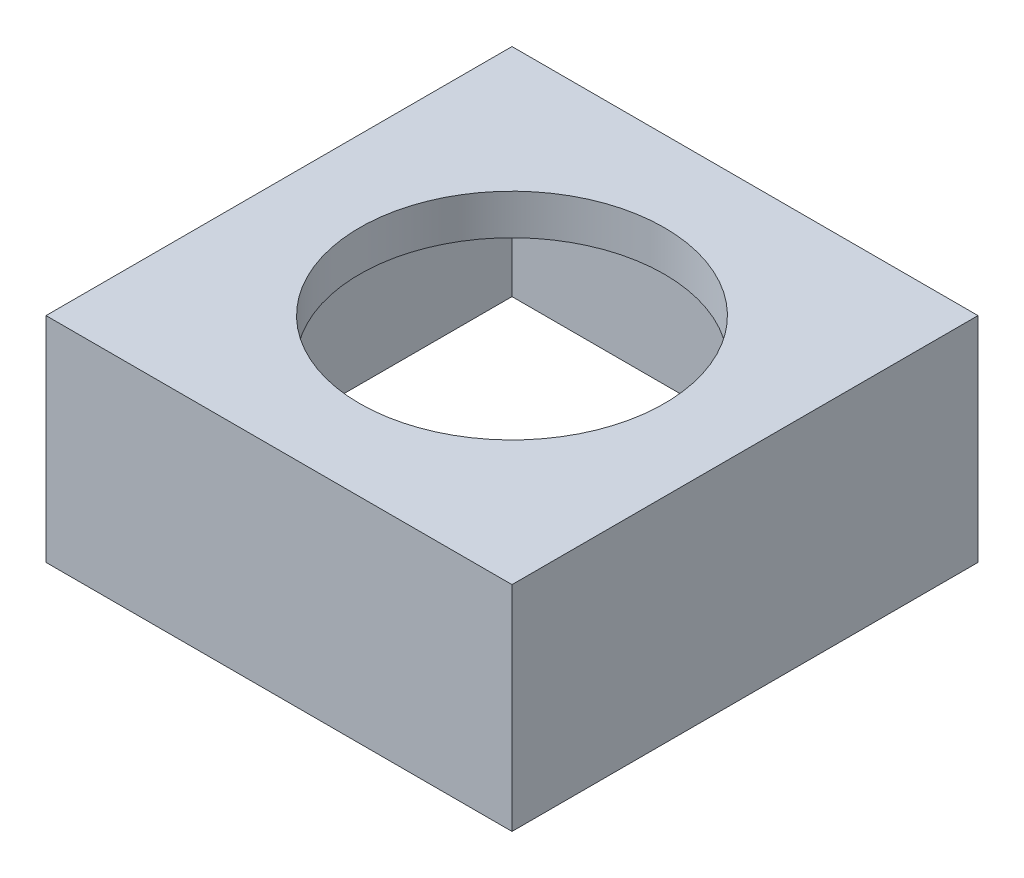
SolidWorks part; units mm, degrees
ref_plane "Front Plane" through (0, 0, 0) normal (0, 0, 1) x (1, 0, 0)
ref_plane "Top Plane" through (0, 0, 0) normal (0, 1, 0) x (1, 0, 0)
ref_plane "Right Plane" through (0, 0, 0) normal (1, 0, 0) x (0, 0, -1)
sketch "Sketch1" plane through (0, 0, 0) normal (0, 1, 0) x (1, 0, 0)
  line L1 (-248.5, -248.5) -> (248.5, -248.5)
  line L2 (-248.5, -248.5) -> (-248.5, 248.5)
  line L3 (-248.5, 248.5) -> (248.5, 248.5)
  line L4 (248.5, -248.5) -> (248.5, 248.5)
  line L5 (-248.5, -248.5) -> (248.5, 248.5) construction
  line L6 (-248.5, 248.5) -> (248.5, -248.5) construction
  line L7 (-245.5, -245.5) -> (245.5, -245.5)
  line L8 (-245.5, -245.5) -> (-245.5, 245.5)
  line L9 (-245.5, 245.5) -> (245.5, 245.5)
  line L10 (245.5, -245.5) -> (245.5, 245.5)
  line L11 (-245.5, -245.5) -> (245.5, 245.5) construction
  line L12 (-245.5, 245.5) -> (245.5, -245.5) construction
  point P0 (0, 0)
  point P5 (0, 0)
  dimension "D1" = 3
  dimension "D2" = 491
extrude "Boss-Extrude1" add sketch "Sketch1" along normal blind 225
sketch "Sketch2" plane through (0, 225, 0) normal (0, 1, 0) x (1, 0, 0)
  line L4 (248.5, -248.5) -> (248.5, 248.5)
  line L5 (248.5, 248.5) -> (-248.5, 248.5)
  line L6 (-248.5, 248.5) -> (-248.5, -248.5)
  line L7 (-248.5, -248.5) -> (248.5, -248.5)
  line L8 (248.5, -248.5) -> (248.5, 248.5)
  line L9 (248.5, 248.5) -> (-248.5, 248.5)
  line L10 (-248.5, 248.5) -> (-248.5, -248.5)
  line L11 (-248.5, -248.5) -> (248.5, -248.5)
  dimension "D1" = 0
extrude "Boss-Extrude2" add sketch "Sketch2" along normal blind 3
sketch "Sketch3" plane through (0, 228, 0) normal (0, 1, 0) x (1, 0, 0)
  circle A0 centre (0, 0) radius 162.5
  dimension "D1" = 325
extrude "Cut-Extrude1" cut sketch "Sketch3" against normal up to next
sketch "Sketch4" plane through (0, 225, 0) normal (0, -1, 0) x (1, 0, 0)
  line L4 (245.5, -245.5) -> (245.5, 245.5)
  line L5 (245.5, 245.5) -> (-245.5, 245.5)
  line L6 (-245.5, 245.5) -> (-245.5, -245.5)
  line L7 (-245.5, -245.5) -> (245.5, -245.5)
  line L8 (245.5, -245.5) -> (245.5, 245.5)
  line L9 (245.5, 245.5) -> (-245.5, 245.5)
  line L10 (-245.5, 245.5) -> (-245.5, -245.5)
  line L11 (-245.5, -245.5) -> (245.5, -245.5)
  circle A0 centre (0, 0) radius 166
  circle A1 centre (0, 0) radius 162.5 construction
  circle A2 centre (0, 0) radius 162.5
  dimension "D2" = 3.5
  dimension "D1" = 0
extrude "Boss-Extrude3" add sketch "Sketch4" along normal blind 40 contours A0 | A2
